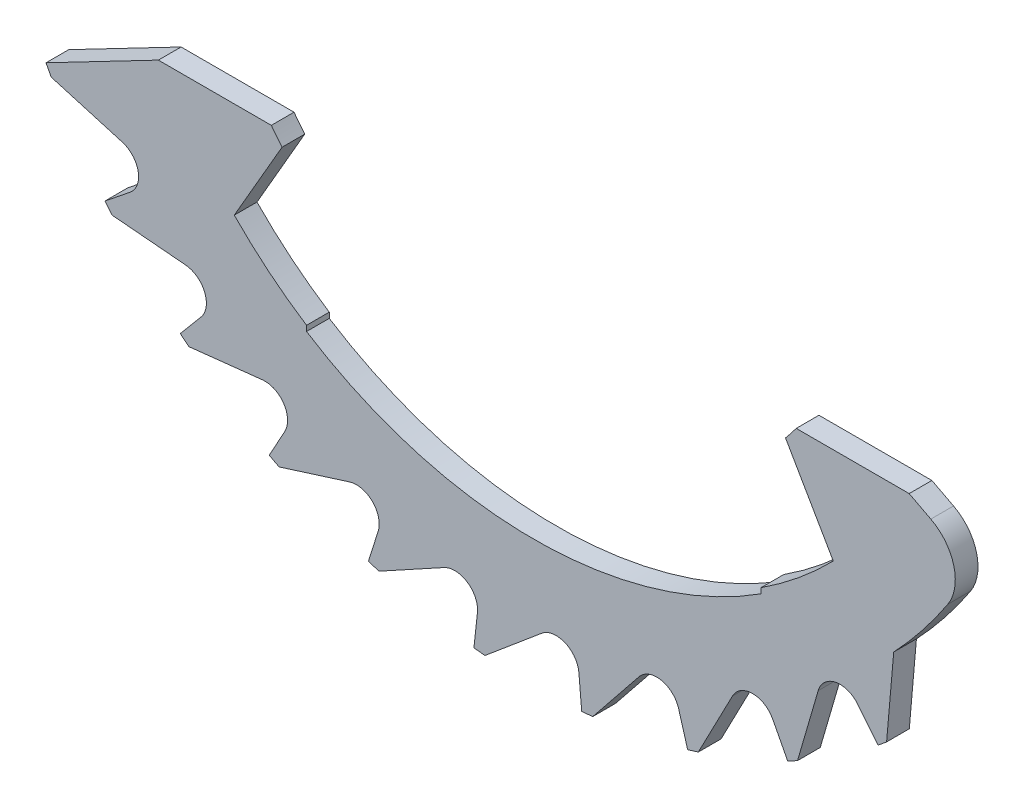
SolidWorks part; units mm, degrees
ref_plane "Front Plane" through (0, 0, 0) normal (0, 0, 1) x (1, 0, 0)
ref_plane "Top Plane" through (0, 0, 0) normal (0, 1, 0) x (1, 0, 0)
ref_plane "Right Plane" through (0, 0, 0) normal (1, 0, 0) x (0, 0, -1)
sketch "Sketch1" plane through (0, 0, 0) normal (0, 0, 1) x (1, 0, 0)
  line L0 (-8.2602, -4.3) -> (-10.7328, -5.5872)
  line L1 (0, 0) -> (0, -12.1) construction
  line L2 (8.2602, -4.3) -> (10.7328, -5.5872)
  line L3 (-5.5392, -4.5997) -> (-6.59, -6.4196)
  line L4 (-8.2602, -4.3) -> (-5.7749, -4.3)
  line L5 (-5, -7.7227) -> (-5, -7.8416)
  line L6 (5.5392, -4.5997) -> (6.59, -6.4196)
  line L8 (-5, 0) -> (-5, -17.1) construction
  line L9 (-5, -17.1) -> (12.3158, -17.1) construction
  line L11 (5, -7.7227) -> (5, -7.8416)
  line L12 (0, -12.1) -> (12.3158, -12.1) construction
  line L13 (5.7749, -4.3) -> (8.2602, -4.3)
  arc A0 (5.7749, -4.3) -> (5.5392, -4.5997) centre (0, 0) cw
  arc A1 (-6.59, -6.4196) -> (-5, -7.7227) centre (0, 0) ccw
  arc A2 (-10.016, -4.3) -> (10.016, -4.3) centre (0, 0) ccw construction
  arc A3 (-10.7328, -5.5872) -> (10.7328, -5.5872) centre (0, 0) ccw
  arc A4 (5, -7.7227) -> (6.59, -6.4196) centre (0, 0) ccw
  circle A5 centre (0, 0) radius 12.1 construction
  circle A6 centre (0, 0) radius 9.2 construction
  arc A7 (-5, -7.8416) -> (5, -7.8416) centre (0, 0) ccw
  arc A8 (-5.7749, -4.3) -> (-5.5392, -4.5997) centre (0, 0) ccw
  point P1 (8.798, 2.6898)
  point P13 (12.1, 0)
  dimension "D1" = 9.3
  dimension "D2" = 9.2
  dimension "D3" = 10.9
  dimension "D10" = 7.2
  dimension "D4" = 2.9
  dimension "D5" = 125
  dimension "D6" = 7.8
  dimension "D9" = 13.18
  dimension "D8" = 30
  dimension "D7" = 10
extrude "Boss-Extrude1" add sketch "Sketch1" along normal blind 0.5
sketch "Sketch2" plane through (0, 0, 0.5) normal (0, 0, 1) x (1, 0, 0)
  line L0 (0, 0) -> (-9.4366, -7.5737) construction
  line L2 (-8.2602, -4.3) -> (-10.7328, -5.5872) construction
  line L3 (-10.6175, -5.8033) -> (-9.0552, -6.2587)
  line L4 (-8.8821, -7.1287) -> (-9.4366, -7.5737)
  arc A0 (-10.7328, -5.5872) -> (10.7328, -5.5872) centre (0, 0) ccw construction
  arc A1 (-8.8901, -6.3068) -> (-8.5007, -6.8226) centre (0, 0) ccw construction
  arc A2 (-8.8821, -7.1287) -> (-9.0552, -6.2587) centre (-9.1951, -6.7387) ccw
  arc A3 (-10.6175, -5.8033) -> (-9.4366, -7.5737) centre (0, 0) ccw
  dimension "D2" = 10.9
  dimension "D3" = 1
  dimension "D1" = 11.25
  dimension "D4" = 55
extrude "Cut-Extrude1" cut sketch "Sketch2" against normal up to next
pattern_circular "CirPattern1" count 10 every 11.25 about axis through (0, 0, 0) along (0, 0, 1) of "Cut-Extrude1"
sketch "Sketch3" plane through (0, 0, 0.5) normal (0, 0, 1) x (1, 0, 0)
  line L0 (7.905, -7.6602) -> (7.7632, -9.2813) construction
  line L1 (0, 0) -> (5.5392, -4.5997) construction
  line L2 (7.92, -7.4889) -> (7.7632, -9.2813)
  line L3 (10.7328, -5.5872) -> (8.2602, -4.3) construction
  line L4 (10.7328, -5.5872) -> (9.6684, -5.0331)
  arc A0 (9.6684, -5.0331) -> (7.92, -7.4889) centre (0, 0) cw
  arc A1 (7.1287, -8.8821) -> (6.2587, -9.0552) centre (6.7387, -9.1951) ccw construction
  arc A4 (8.7245, -7.3207) -> (7.905, -7.6602) centre (8.4031, -7.7037) ccw construction
  arc A5 (9.2691, -7.7777) -> (10.7328, -5.5872) centre (0, 0) ccw construction
  arc A6 (7.7632, -9.2813) -> (10.7328, -5.5872) centre (0, 0) ccw
extrude "Cut-Extrude3" cut sketch "Sketch3" against normal up to next
fillet "Fillet3" radius 1 1 edges at (9.6684, -5.0331, 0.25)
